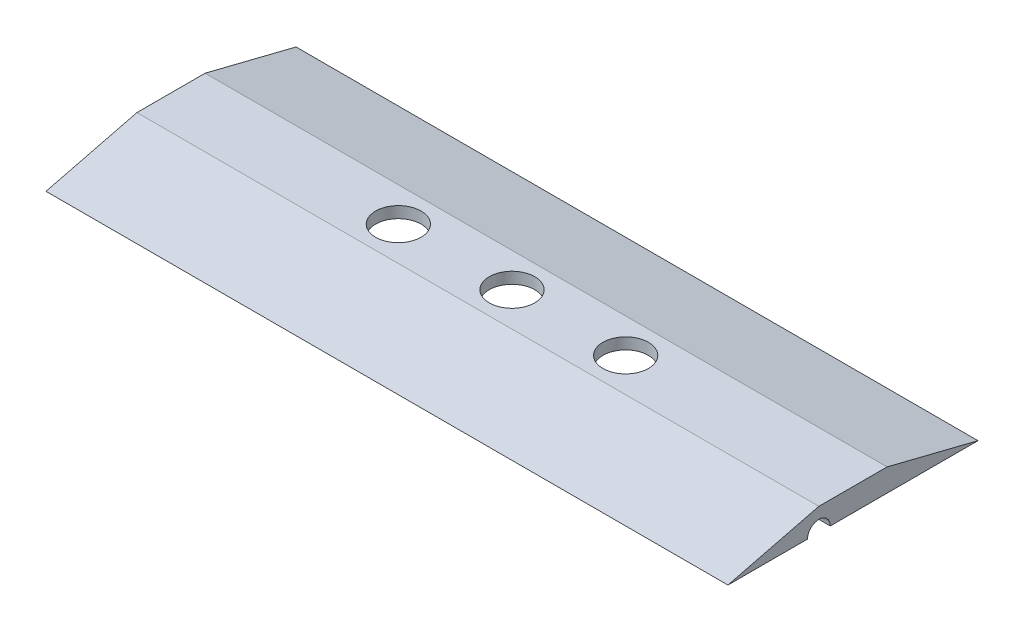
SolidWorks part; units mm, degrees
ref_plane "Plan de face" through (0, 0, 0) normal (0, 0, 1) x (1, 0, 0)
ref_plane "Plan de dessus" through (0, 0, 0) normal (0, 1, 0) x (1, 0, 0)
ref_plane "Plan de droite" through (0, 0, 0) normal (1, 0, 0) x (0, 0, -1)
sketch "Esquisse2" plane through (0, 0, 0) normal (1, 0, 0) x (0, 0, -1)
  line L0 (15, 0) -> (55, 0)
  line L1 (-15, 10) -> (15, 10)
  line L3 (-15, 0) -> (15, 0)
  line L5 (55, 0) -> (15, 10)
  line L6 (-15, 0) -> (-55, 0)
  line L7 (-55, 0) -> (-15, 10)
  point P7 (0, 0)
  dimension "D1" = 30
  dimension "D2" = 10
  dimension "D3" = 40
  dimension "D4" = 40
  dimension "D5" = 0
extrude "Boss.-Extru.1" add sketch "Esquisse2" along normal mid plane 300
sketch "Esquisse3" plane through (-150, 0, 0) normal (-1, 0, 0) x (0, 0, 1)
  line L0 (55, 0) -> (-55, 0) construction
  circle A0 centre (15, 0) radius 5
  dimension "D1" = 10
  dimension "D2" = 15
extrude "Enlèv. mat.-Extru.1" cut sketch "Esquisse3" against normal through all
sketch "Esquisse5" plane through (0, 10, 0) normal (0, 1, 0) x (1, 0, 0)
  line L0 (0, -5.5) -> (0, 5.5) construction
  line L1 (150, -15) -> (-150, -15) construction
  circle A0 centre (0, 0) radius 10
  circle A1 centre (50, 0) radius 10
  circle A5 centre (-50, 0) radius 10
  dimension "D1" = 20
  dimension "D3" = 50
  dimension "D4" = 15
  dimension "D2" = 2
extrude "Enlèv. mat.-Extru.2" cut sketch "Esquisse5" against normal through all
sketch "Esquisse6" plane through (0, 0, 0) normal (0, -1, 0) x (1, 0, 0)
  line L1 (-75, 15) -> (75, 15)
  line L2 (-75, 15) -> (-75, -15)
  line L3 (-75, -15) -> (75, -15)
  line L4 (75, 15) -> (75, -15)
  circle A0 centre (-66.4243, 0) radius 2.5
  circle A1 centre (-31.4243, 0) radius 2.5
  circle A2 centre (-16.4243, 0) radius 2.5
  circle A3 centre (18.5757, 0) radius 2.5
  circle A4 centre (33.5757, 0) radius 2.5
  circle A5 centre (68.5757, 0) radius 2.5
  point P12 (-48.9243, 0)
  point P20 (0, 0)
  dimension "D5" = 5
  dimension "D8" = 17.5
  dimension "D1" = 150
  dimension "D2" = 30
  dimension "D3" = 15
  dimension "D4" = 75
  dimension "D7" = 3
  dimension "D6" = 2
extrude "Enlèv. mat.-Extru.3" cut sketch "Esquisse6" against normal blind 5
